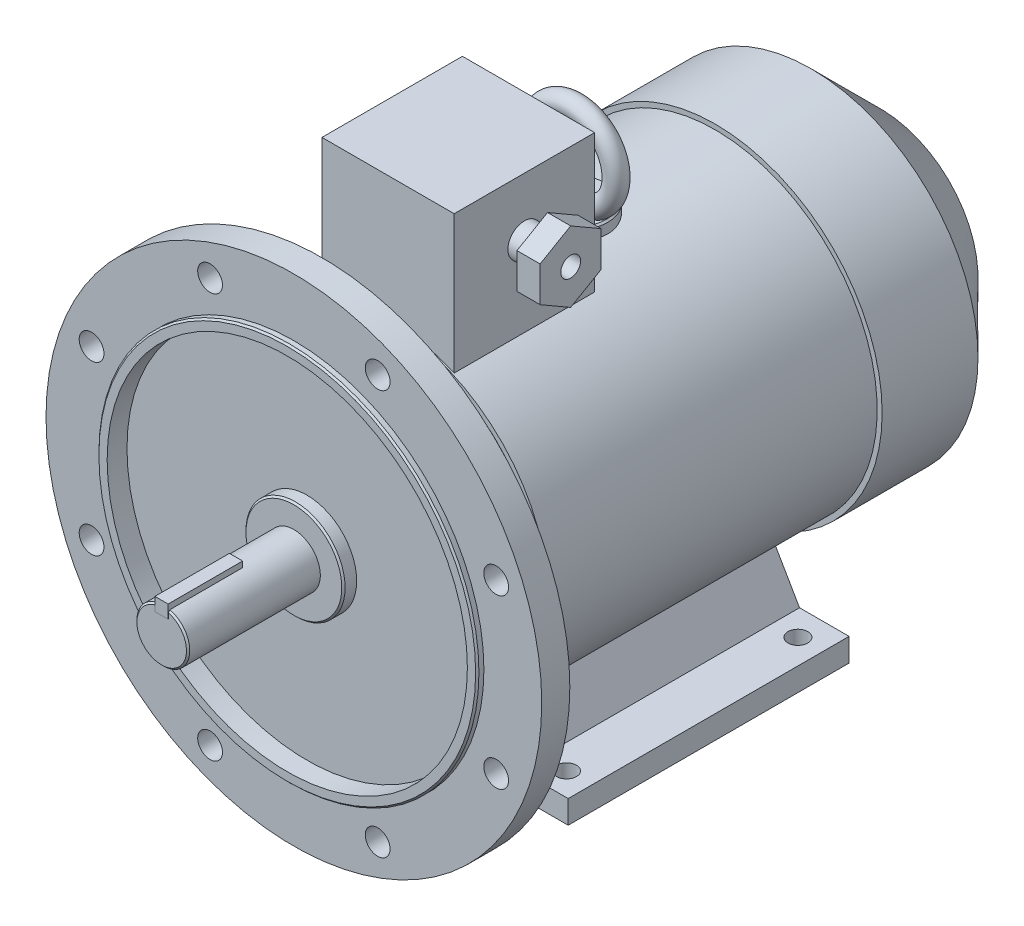
SolidWorks part; units mm, degrees
material "Ст.3 ГОСТ 380-88"
ref_plane "Спереди" through (0, 0, 0) normal (0, 0, 1) x (1, 0, 0)
ref_plane "Сверху" through (0, 0, 0) normal (0, 1, 0) x (1, 0, 0)
ref_plane "Справа" through (0, 0, 0) normal (1, 0, 0) x (0, 0, -1)
sketch "Эскиз1" plane through (0, 0, 0) normal (0, 0, 1) x (1, 0, 0)
  circle A0 centre (0, 0) radius 16
  dimension "D1" = 32
extrude "Вытянуть1" add sketch "Эскиз1" along normal blind 80
sketch "Эскиз2" plane through (0, 0, 0) normal (0, 0, -1) x (-1, 0, 0)
  circle A0 centre (0, 0) radius 150
  dimension "D1" = 300
extrude "Вытянуть2" add sketch "Эскиз2" along normal blind 17
sketch "Эскиз3" plane through (0, 0, 80) normal (0, 0, 1) x (1, 0, 0)
  line L0 (0, 0) -> (0, 28.3805) construction
  line L2 (-4, 19) -> (4, 19)
  line L3 (-4, 19) -> (-4, 11)
  line L4 (-4, 11) -> (4, 11)
  line L5 (4, 19) -> (4, 11)
  circle A2 centre (0, 0) radius 16 construction
  dimension "D1" = 8
  dimension "D2" = 8
  dimension "D3" = 35
extrude "Вытянуть3" add sketch "Эскиз3" against normal blind 45 and the other way blind 0.1
sketch "Эскиз4" plane through (0, 0, 0) normal (0, 0, 1) x (1, 0, 0)
  circle A0 centre (0, 0) radius 115
  circle A1 centre (0, 0) radius 109
  dimension "D1" = 230
  dimension "D2" = 218
extrude "Вытянуть4" add sketch "Эскиз4" along normal blind 4
sketch "Эскиз5" plane through (0, 0, 0) normal (0, 0, 1) x (1, 0, 0)
  circle A0 centre (0, 0) radius 109
  circle A1 centre (0, 0) radius 30
  dimension "D1" = 218
  dimension "D2" = 60
extrude "Вырез-Вытянуть1" cut sketch "Эскиз5" against normal blind 8
chamfer "Фаска1" distance 1 angle 45 3 edges at (0, -16, 80) (30, 0, 0) (115, 0, 4)
sketch "Эскиз6" plane through (0, 0, 0) normal (0, 0, 1) x (1, 0, 0)
  line L0 (0, 0) -> (0, 187.3141) construction
  line L1 (0, 0) -> (-70.131, 169.3113) construction
  circle A0 centre (-50.7056, 122.414) radius 7.5
  circle A3 centre (50.7056, 122.414) radius 7.5
  circle A4 centre (122.414, 50.7056) radius 7.5
  circle A5 centre (122.414, -50.7056) radius 7.5
  circle A6 centre (50.7056, -122.414) radius 7.5
  circle A7 centre (-50.7056, -122.414) radius 7.5
  circle A8 centre (-122.414, -50.7056) radius 7.5
  circle A9 centre (-122.414, 50.7056) radius 7.5
  dimension "D2" = 15
  dimension "D1" = 22.5
  dimension "D3" = 132.5
  dimension "D4" = 132.5
  dimension "D5" = 132.5
extrude "Вырез-Вытянуть2" cut sketch "Эскиз6" against normal through all
sketch "Эскиз7" plane through (0, 0, -17) normal (0, 0, -1) x (-1, 0, 0)
  circle A0 centre (0, 0) radius 95
  dimension "D1" = 190
extrude "Вытянуть5" add sketch "Эскиз7" along normal blind 39
sketch "Эскиз8" plane through (0, 0, -56) normal (0, 0, -1) x (-1, 0, 0)
  circle A0 centre (0, 0) radius 98
  dimension "D1" = 196
extrude "Вытянуть6" add sketch "Эскиз8" along normal blind 199
sketch "Эскиз9" plane through (0, 0, -255) normal (0, 0, -1) x (-1, 0, 0)
  circle A0 centre (0, 0) radius 101
  dimension "D1" = 202
extrude "Вытянуть7" add sketch "Эскиз9" along normal blind 100
chamfer "Фаска2" distance 42 angle 45 1 edges at (-101, 0, -355)
sketch "Эскиз10" plane through (0, 0, -56) normal (0, 0, 1) x (1, 0, 0)
  line L0 (0, 0) -> (0, -223.3518) construction
  line L1 (-110, -112) -> (-71.9171, -112)
  line L2 (-71.9171, -112) -> (-51.4404, -76.5333)
  line L3 (-51.4404, -76.5333) -> (-63.5648, -69.5333)
  line L4 (-63.5648, -69.5333) -> (-80, -98)
  line L5 (-80, -98) -> (-110, -98)
  line L6 (-110, -98) -> (-110, -112)
  line L7 (110, -98) -> (110, -112)
  line L8 (80, -98) -> (110, -98)
  line L9 (63.5648, -69.5333) -> (80, -98)
  line L10 (51.4404, -76.5333) -> (63.5648, -69.5333)
  line L11 (71.9171, -112) -> (51.4404, -76.5333)
  line L12 (110, -112) -> (71.9171, -112)
  dimension "D1" = 14
  dimension "D2" = 14
  dimension "D3" = 30
  dimension "D4" = 110
  dimension "D5" = 80
  dimension "D6" = 112
  dimension "D7" = 92
extrude "Вытянуть8" add sketch "Эскиз10" against normal blind 170
sketch "Эскиз11" plane through (0, -112, 0) normal (0, -1, 0) x (1, 0, 0)
  line L0 (-95, -70) -> (136.4638, -70) construction
  line L1 (15, 80) -> (-15, 80) construction
  line L2 (0, 0) -> (0, -248.1958) construction
  line L3 (95, -70) -> (-95, -70) construction
  line L4 (95, -70) -> (95, -210) construction
  circle A0 centre (95, -70) radius 6
  circle A1 centre (-95, -70) radius 6
  circle A2 centre (95, -210) radius 6
  circle A3 centre (-95, -210) radius 6
  dimension "D2" = 12
  dimension "D5" = 140
  dimension "D1" = 150
  dimension "D3" = 95
  dimension "D4" = 90
  dimension "D6" = 190
  dimension "D7" = 190
  dimension "D8" = 70
  dimension "D9" = 210
extrude "Вырез-Вытянуть3" cut sketch "Эскиз11" against normal up to next
sketch "Эскиз12" plane through (0, 0, 0) normal (0, 1, 0) x (1, 0, 0)
  line L0 (0, 0) -> (0, 375.5268) construction
  line L2 (-40, 57) -> (40, 57)
  line L3 (-40, 57) -> (-40, 142)
  line L4 (-40, 142) -> (40, 142)
  line L5 (40, 57) -> (40, 142)
  line L6 (-98, 56) -> (98, 56) construction
  dimension "D1" = 85
  dimension "D2" = 80
  dimension "D3" = 1
extrude "Вытянуть9" add sketch "Эскиз12" along normal blind 173
sketch "Эскиз13" plane through (0, 0, 0) normal (0, 1, 0) x (1, 0, 0)
  line L0 (0, 0) -> (0, 261.3171) construction
  circle A0 centre (0, 170) radius 20
  dimension "D1" = 40
  dimension "D2" = 170
extrude "Вытянуть10" add sketch "Эскиз13" along normal blind 103
chamfer "Фаска3" distance 1 angle 45 1 edges at (0, 103, -150)
ref_plane "Плоскость1" through (0, 0, -170) normal (0, 0, 1) x (1, 0, 0)
sketch "Эскиз14" plane through (0, 0, -170) normal (0, 0, 1) x (1, 0, 0)
  line L0 (19, 103) -> (-19, 103) construction
  line L1 (0, 0) -> (0, 193.8662) construction
  circle A0 centre (0, 128) radius 25
  dimension "D1" = 50
sketch "Эскиз15" plane through (0, 0, 0) normal (1, 0, 0) x (0, 0, -1)
  line L0 (170, 153) -> (170, 103) construction
  line L1 (189, 103) -> (151, 103) construction
  circle A0 centre (170, 153) radius 6
  dimension "D1" = 12
  dimension "D2" = 50
sweep "По траектории1" add profiles "Эскиз15" path "Эскиз14"
sketch "Эскиз16" plane through (40, 0, 0) normal (1, 0, 0) x (0, 0, -1)
  line L0 (57, 173) -> (142, 173) construction
  line L1 (57, 173) -> (57, 89.4651) construction
  circle A0 centre (99.5, 138) radius 10
  dimension "D1" = 20
  dimension "D2" = 35
  dimension "D3" = 42.5
extrude "Вытянуть11" add sketch "Эскиз16" along normal blind 14
sketch "Эскиз17" plane through (54, 0, 0) normal (1, 0, 0) x (0, 0, -1)
  line L1 (99.5, 159.362) -> (81, 148.681)
  line L2 (81, 148.681) -> (81, 127.319)
  line L3 (81, 127.319) -> (99.5, 116.638)
  line L4 (99.5, 116.638) -> (118, 127.319)
  line L5 (118, 127.319) -> (118, 148.681)
  line L6 (118, 148.681) -> (99.5, 159.362)
  line L7 (99.5, 138) -> (99.5, 180.1702) construction
  circle A0 centre (99.5, 138) radius 18.5 construction
  circle A1 centre (99.5, 138) radius 10 construction
  dimension "D1" = 37
extrude "Вытянуть12" add sketch "Эскиз17" along normal blind 14
sketch "Эскиз18" plane through (68, 0, 0) normal (1, 0, 0) x (0, 0, -1)
  circle A0 centre (99.5, 138) radius 6
  circle A1 centre (99.5, 138) radius 10 construction
  dimension "D1" = 12
extrude "Вырез-Вытянуть4" cut sketch "Эскиз18" against normal blind 14
